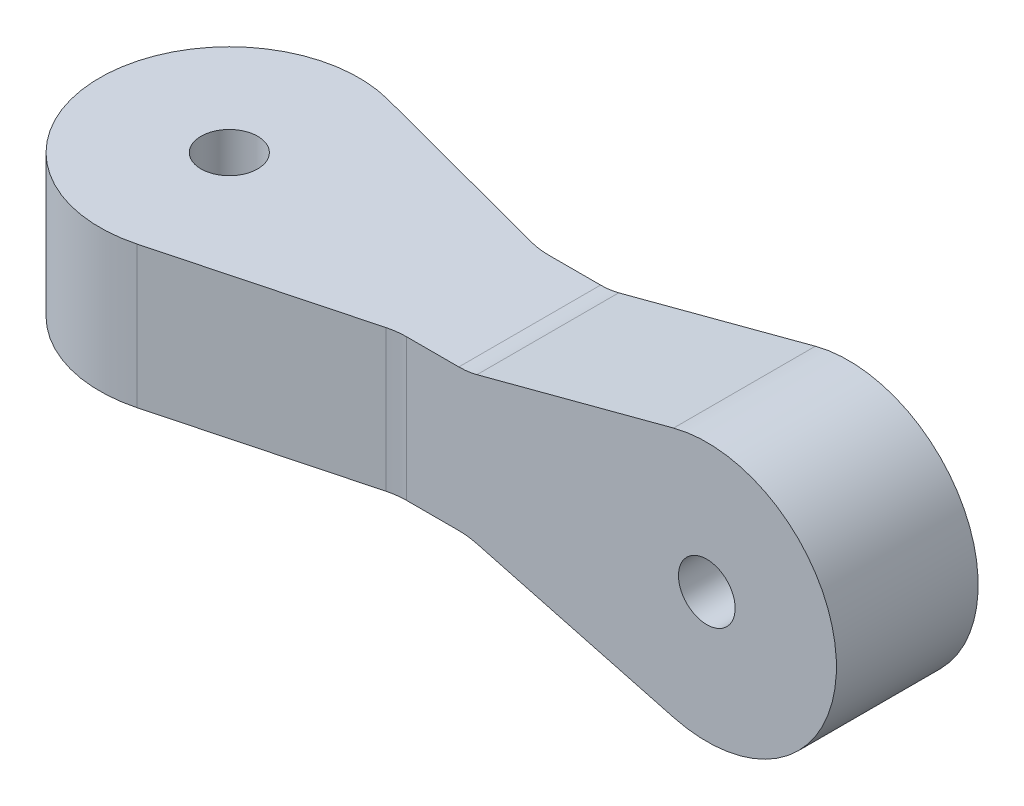
SolidWorks part; units mm, degrees
ref_plane "Ön Düzlem" through (0, 0, 0) normal (0, 0, 1) x (1, 0, 0)
ref_plane "Üst Düzlem" through (0, 0, 0) normal (0, 1, 0) x (1, 0, 0)
ref_plane "Sağ Düzlem" through (0, 0, 0) normal (1, 0, 0) x (0, 0, -1)
sketch "Sketch1" plane through (0, 0, 0) normal (0, 0, 1) x (1, 0, 0)
  line L0 (-4.6832, 17.6811) -> (-33.6832, 10)
  line L1 (-4.6832, -17.6811) -> (-33.6832, -10)
  line L2 (-33.6832, 10) -> (-33.6832, -10)
  line L3 (0, 0) -> (-33.6832, 0) construction
  line L4 (-4.6832, -17.6811) -> (-4.6832, 17.6811) construction
  arc A0 (-4.6832, 17.6811) -> (-4.6832, -17.6811) centre (0, 0) cw
  circle A1 centre (0, 0) radius 4
  point P10 (-33.6832, 0)
  dimension "D1" = 8
  dimension "D2" = 20
  dimension "D3" = 30
  dimension "D4" = 29
extrude "Boss-Extrude1" add sketch "Sketch1" against normal mid plane 20
sketch "Sketch2" plane through (-33.6832, 0, 0) normal (-1, 0, 0) x (0, 0, 1)
  line L4 (10, -10) -> (10, 10)
  line L5 (10, 10) -> (-10, 10)
  line L6 (-10, 10) -> (-10, -10)
  line L7 (-10, -10) -> (10, -10)
  line L8 (10, -10) -> (10, 10)
  line L9 (10, 10) -> (-10, 10)
  line L10 (-10, 10) -> (-10, -10)
  line L11 (-10, -10) -> (10, -10)
  dimension "D1" = 0
extrude "Boss-Extrude2" add sketch "Sketch2" along normal blind 10
sketch "Sketch3" plane through (0, 0, 0) normal (0, 1, 0) x (1, 0, 0)
  line L0 (-43.6832, 10) -> (-72.6832, 17.6811)
  line L1 (-43.6832, -10) -> (-72.6832, -17.6811)
  line L2 (0, 0) -> (-77.3663, 0) construction
  line L3 (-72.6832, 17.6811) -> (-72.6832, -17.6811) construction
  line L6 (-43.6832, -10) -> (-43.6832, 10) construction
  line L7 (-43.6832, 10) -> (-43.6832, -10)
  line L11 (-33.6832, -10) -> (-33.6832, 10)
  line L12 (-33.6832, 10) -> (-43.6832, 10)
  line L13 (-43.6832, 10) -> (-43.6832, -10)
  line L14 (-43.6832, -10) -> (-33.6832, -10)
  line L17 (-43.6832, 10) -> (-43.6832, 10.0034)
  arc A0 (-72.6832, 17.6811) -> (-72.6832, -17.6811) centre (-77.3663, 0) ccw
  circle A1 centre (-77.3663, 0) radius 4
  dimension "D4" = 8
  dimension "D1" = 30
  dimension "D2" = 29
  dimension "D3" = 0
extrude "Boss-Extrude4" add sketch "Sketch3" against normal mid plane 20 contours L0 A0 L1 L7 A1
fillet "Fillet1" radius 10 4 edges at (-33.6832, -10, 0) (-33.6832, 10, 0) (-43.6832, 0, -10) (-43.6832, 0, 10)
